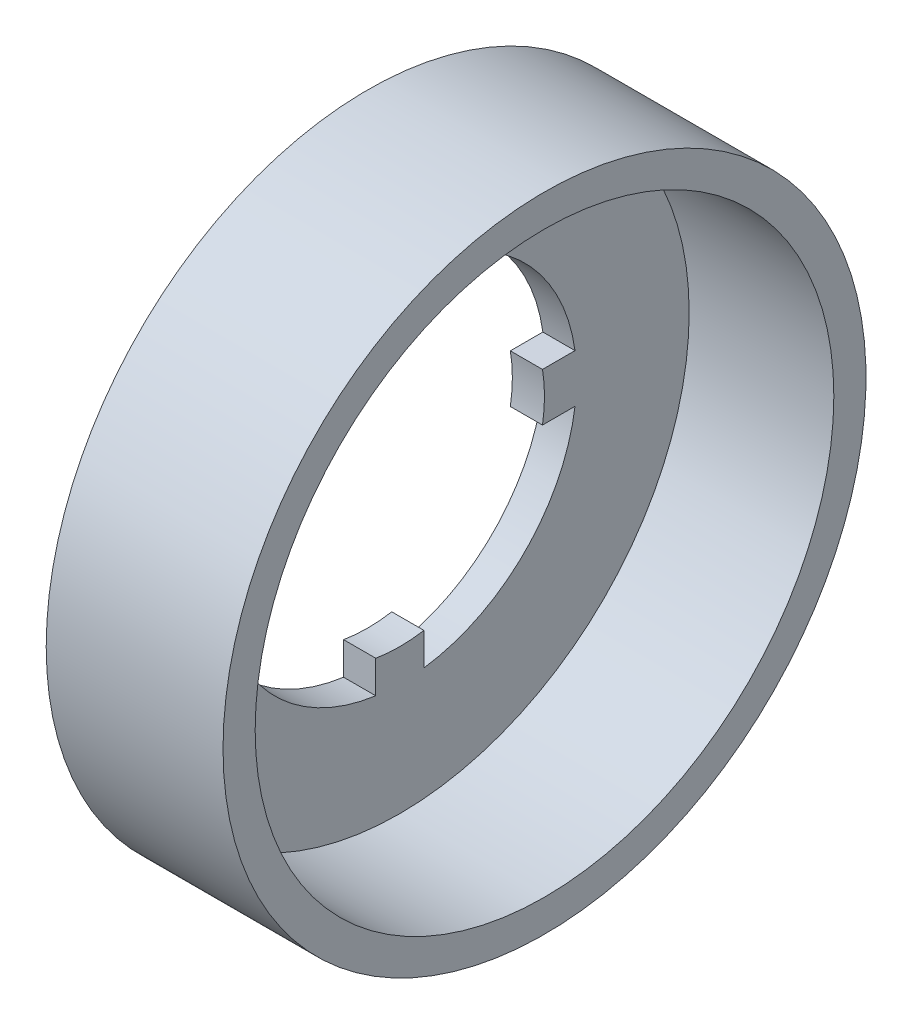
SolidWorks part; units mm, degrees
ref_plane "Plan1" through (0, 0, 0) normal (0, 0, 1) x (1, 0, 0)
ref_plane "Plan2" through (0, 0, 0) normal (0, 1, 0) x (1, 0, 0)
ref_plane "Plan3" through (0, 0, 0) normal (1, 0, 0) x (0, 0, -1)
sketch "Esquisse1" plane through (0, 0, 0) normal (0, 0, 1) x (1, 0, 0)
  line L0 (0, 40) -> (0, 18)
  line L1 (0, 18) -> (4, 18)
  line L2 (4, 18) -> (4, 36)
  line L3 (4, 36) -> (22, 36)
  line L4 (22, 36) -> (22, 40)
  line L5 (22, 40) -> (0, 40)
  line L6 (0, 0) -> (55, 0) construction
  dimension "D1" = 40
  dimension "D2" = 36
  dimension "D3" = 4
  dimension "D4" = 18
  dimension "D5" = 22
revolve "Base-Révolution" add sketch "Esquisse1" angle 360 about L6
sketch "Esquisse2" plane through (0, 0, 0) normal (-1, 0, 0) x (0, 0, 1)
  line L0 (-3, 16) -> (-3, 21.7945)
  line L1 (3, 16) -> (3, 21.7945)
  line L2 (-3, 16) -> (3, 16)
  line L3 (16, 3) -> (21.7945, 3)
  line L4 (16, -3) -> (21.7945, -3)
  line L5 (16, 3) -> (16, -3)
  line L6 (3, -16) -> (3, -21.7945)
  line L7 (-3, -16) -> (-3, -21.7945)
  line L8 (3, -16) -> (-3, -16)
  line L9 (-16, -3) -> (-21.7945, -3)
  line L10 (-16, 3) -> (-21.7945, 3)
  line L11 (-16, -3) -> (-16, 3)
  arc A0 (-3, 21.7945) -> (-21.7945, 3) centre (0, 0) ccw
  arc A1 (21.7945, 3) -> (3, 21.7945) centre (0, 0) ccw
  arc A2 (3, -21.7945) -> (21.7945, -3) centre (0, 0) ccw
  arc A3 (-21.7945, -3) -> (-3, -21.7945) centre (0, 0) ccw
  dimension "D2" = 44
  dimension "D1" = 6
  dimension "D3" = 3
  dimension "D4" = 16
extrude "Enlèv. mat.-Extru.1" cut sketch "Esquisse2" against normal through all
